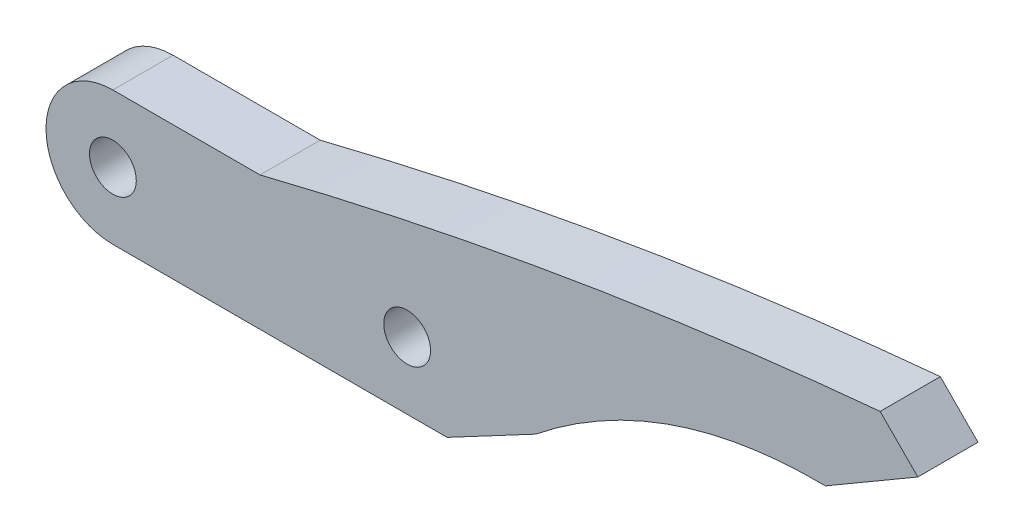
SolidWorks part; units mm, degrees
ref_plane "Front Plane" through (0, 0, 0) normal (0, 0, 1) x (1, 0, 0)
ref_plane "Top Plane" through (0, 0, 0) normal (0, 1, 0) x (1, 0, 0)
ref_plane "Right Plane" through (0, 0, 0) normal (1, 0, 0) x (0, 0, -1)
sketch "Sketch1" plane through (0, 0, 0) normal (0, 0, 1) x (1, 0, 0)
  line L0 (-11, 0) -> (11, 0) construction
  line L2 (-11, -5) -> (11, -5)
  line L4 (-11, 5) -> (11, 5)
  line L6 (-13.6225, -4.257) -> (13.6225, 4.257) construction
  line L7 (-13.6225, 4.257) -> (13.6225, -4.257) construction
  circle A0 centre (-11, 0) radius 5
  circle A1 centre (-11, 0) radius 1.75
  circle A2 centre (11, 0) radius 1.75
  circle A3 centre (11, 0) radius 5
  point P7 (0, 0)
  dimension "D1" = 3.5
  dimension "D2" = 10
  dimension "D3" = 22
extrude "Boss-Extrude1" add sketch "Sketch1" along normal blind 4.5 contours A0 A1 | A3 L4 A0 L2 | A3 A2
sketch "Sketch2" plane through (0, 0, 4.5) normal (0, 0, 1) x (1, 0, 0)
  line L0 (46.364, 12.87) -> (49.1808, 10.03)
  line L1 (49.1808, 10.03) -> (42.27, 6)
  line L3 (-11, -5) -> (11, -5) construction
  line L4 (11, -5) -> (11, 5) construction
  line L5 (20.61, -1.48) -> (13.99, -5)
  line L6 (13.99, -5) -> (11, -5)
  line L7 (-11, 5) -> (11, 5) construction
  line L8 (0, 5) -> (11, 5)
  arc A0 (11, -5) -> (11, 5) centre (11, 0) ccw construction
  arc A1 (11, -5) -> (11, 5) centre (11, 0) ccw
  spline S0 degree 2 poles (42.27, 6) (30.1462, 6.1573) (20.61, -1.48) knots 0 0 0 1 1 1
  spline S1 degree 2 poles (0, 5) (22.8855, 10.7079) (46.364, 12.87) knots 0 0 0 1 1 1
  point P13 (11, 0)
  arc M9 (11, -5) -> (11, 5) centre (11, 0) ccw
  line M10 (11, 5) -> (-11, 5)
  dimension "D1" = 8
  dimension "D2" = 4
  dimension "D3" = 11
  dimension "D4" = 15.03
  dimension "D5" = 17.87
  dimension "D6" = 9.45
  dimension "D7" = 3.52
  dimension "D8" = 9.61
  dimension "D9" = 20.52
  dimension "D10" = 31.27
  dimension "D11" = 11
  dimension "D12" = 2.99
  dimension "D13" = 28.001
  dimension "D14" = 13.52
  dimension "D15" = 15.07
extrude "Boss-Extrude2" add sketch "Sketch2" against normal up to surface (4.5 mm away) contours S1 L6 L5 S0 L1 L0 M10 M9 up to face at (-9.25, 0, 0)
